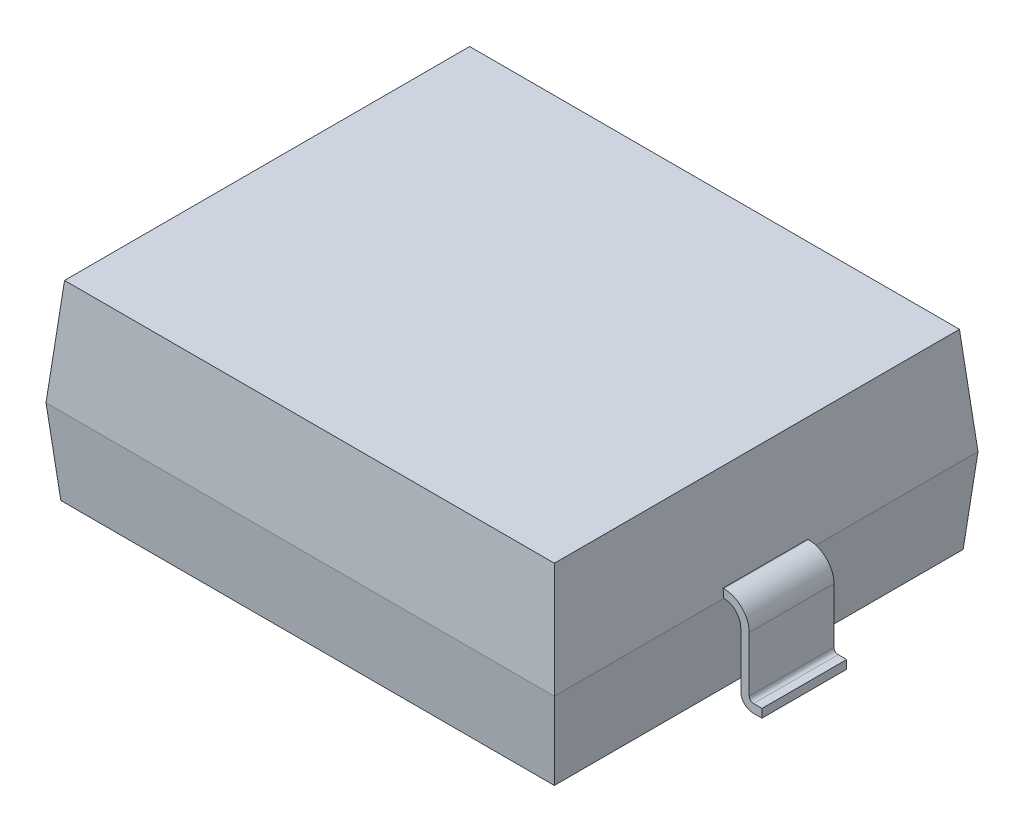
SolidWorks part; units mm, degrees
ref_plane "Front" through (0, 0, 0) normal (0, 0, 1) x (1, 0, 0)
ref_plane "Top" through (0, 0, 0) normal (0, 1, 0) x (1, 0, 0)
ref_plane "Right" through (0, 0, 0) normal (1, 0, 0) x (0, 0, -1)
sketch "Sketch1" plane through (0, 0, 0) normal (0, 1, 0) x (1, 0, 0)
  line L1 (-3, -2.5) -> (3, -2.5)
  line L2 (-3, -2.5) -> (-3, 2.5)
  line L3 (-3, 2.5) -> (3, 2.5)
  line L4 (3, -2.5) -> (3, 2.5)
  line L5 (-3, -2.5) -> (3, 2.5) construction
  line L6 (-3, 2.5) -> (3, -2.5) construction
  point P0 (0, 0)
  dimension "D1" = 6
  dimension "D2" = 5
extrude "Boss-Extrude1" add sketch "Sketch1" along normal blind 1.25 draft 5 and the other way blind 1 draft 5
sketch "Sketch2" plane through (0, 0, 0) normal (0, 0, 1) x (1, 0, 0)
  line L0 (-3.35, -1) -> (-3.45, -1)
  line L1 (-3, 0) -> (3, 0) construction
  line L2 (0, 0) -> (0, -0.2202) construction
  line L3 (-3.2, -0.2) -> (-3.2, -0.85)
  line L4 (-2.9125, -1) -> (2.9125, -1) construction
  line L5 (-3, 0) -> (-1.573, 0)
  arc A0 (-3, 0) -> (-3.2, -0.2) centre (-3, -0.2) ccw
  arc A1 (-3.2, -0.85) -> (-3.35, -1) centre (-3.35, -0.85) cw
  point P6 (0, 0)
  dimension "D1" = 0.2
  dimension "D2" = 0.15
  dimension "D3" = 0.1
extrude "Extrude-Thin1" add sketch "Sketch2" along normal blind 0.5 and the other way blind 0.5 separate body thin
mirror "Mirror3" about plane through (0, 0, 0) normal (1, 0, 0) of bodies 102
